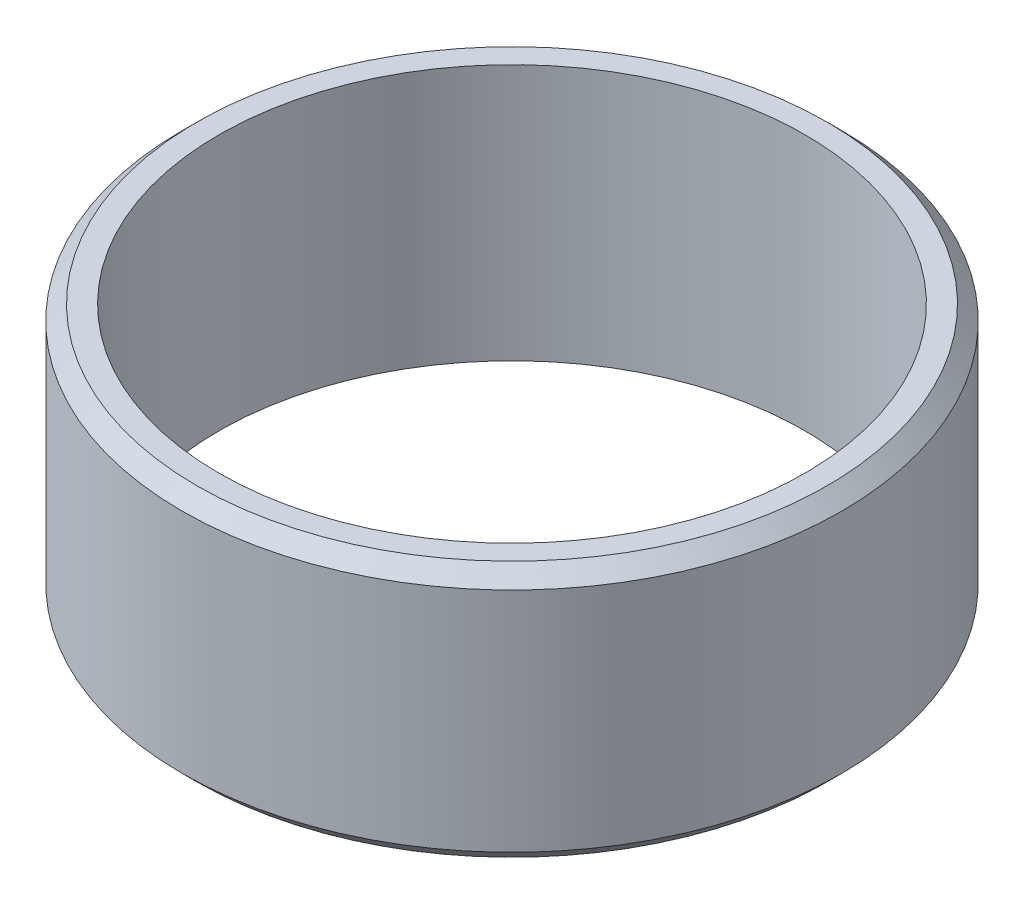
SolidWorks part; units mm, degrees
material "6061-T6 (SS)"
ref_plane "정면" through (0, 0, 0) normal (0, 0, 1) x (1, 0, 0)
ref_plane "윗면" through (0, 0, 0) normal (0, 1, 0) x (1, 0, 0)
ref_plane "우측면" through (0, 0, 0) normal (1, 0, 0) x (0, 0, -1)
sketch "스케치1" plane through (0, 0, 0) normal (0, 1, 0) x (1, 0, 0)
  circle A0 centre (0, 0) radius 4.5
  circle A1 centre (0, 0) radius 4
  dimension "D1" = 8
  dimension "D2" = 9
extrude "보스-돌출1" add sketch "스케치1" along normal blind 3.5
chamfer "모따기1" distance 0.2 angle 45 2 edges at (0, 3.5, 4.5) (0, 0, 4.5)
